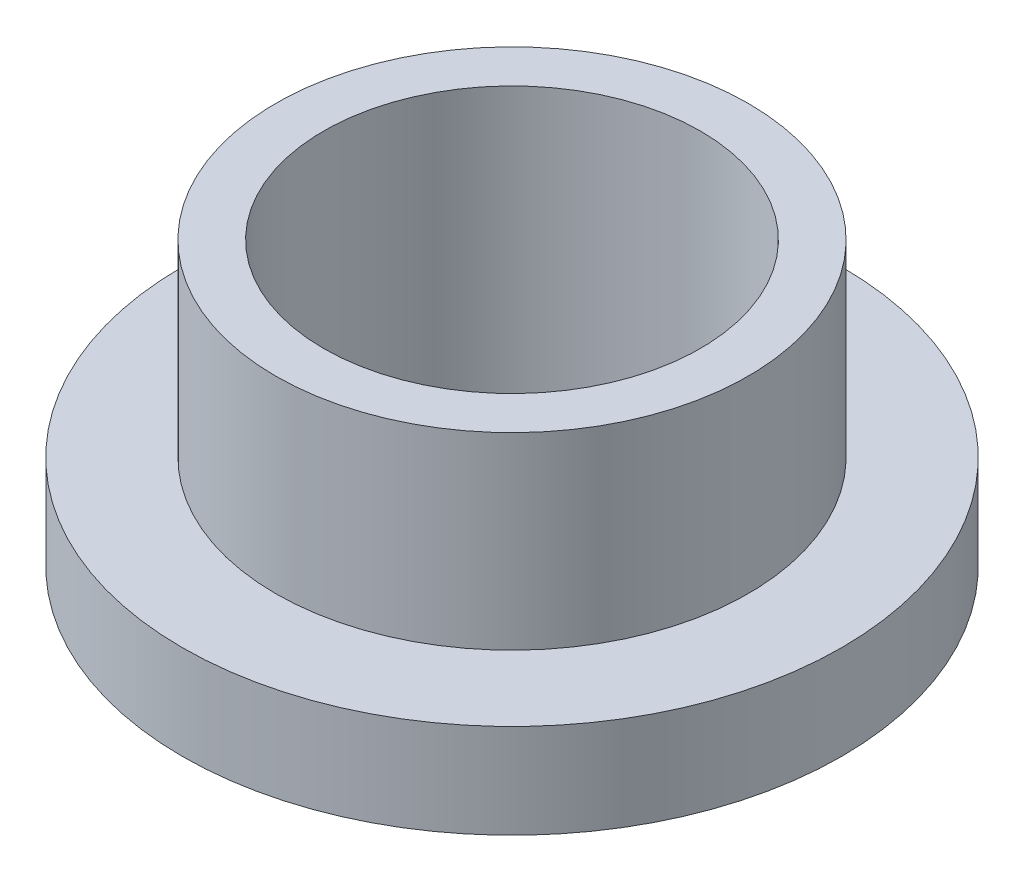
SolidWorks part; units mm, degrees
ref_plane "Front" through (0, 0, 0) normal (0, 0, 1) x (1, 0, 0)
ref_plane "Top" through (0, 0, 0) normal (0, 1, 0) x (1, 0, 0)
ref_plane "Right" through (0, 0, 0) normal (1, 0, 0) x (0, 0, -1)
sketch "Sketch1" plane through (0, 0, 0) normal (0, 1, 0) x (1, 0, 0)
  circle A0 centre (0, 0) radius 6.35
  circle A1 centre (0, 0) radius 7.9629
  circle A2 centre (0, 0) radius 11.1125
  dimension "ID" = 12.7
  dimension "OD" = 15.9258
  dimension "FlangeOD" = 22.225
sketch "Sketch2" plane through (0, 0, 0) normal (0, 1, 0) x (1, 0, 0)
  circle A0 centre (0, 0) radius 6.35 construction
  circle A1 centre (0, 0) radius 7.9629 construction
  circle A2 centre (0, 0) radius 6.35
  circle A3 centre (0, 0) radius 7.9629
extrude "Boss-Extrude1" add sketch "Sketch2" along normal blind 9.525
sketch "Sketch3" plane through (0, 0, 0) normal (0, 1, 0) x (1, 0, 0)
  circle A0 centre (0, 0) radius 11.1125 construction
  circle A1 centre (0, 0) radius 7.9629 construction
  circle A2 centre (0, 0) radius 11.1125
  circle A3 centre (0, 0) radius 7.9629
extrude "Boss-Extrude2" add sketch "Sketch3" along normal blind 3.175
